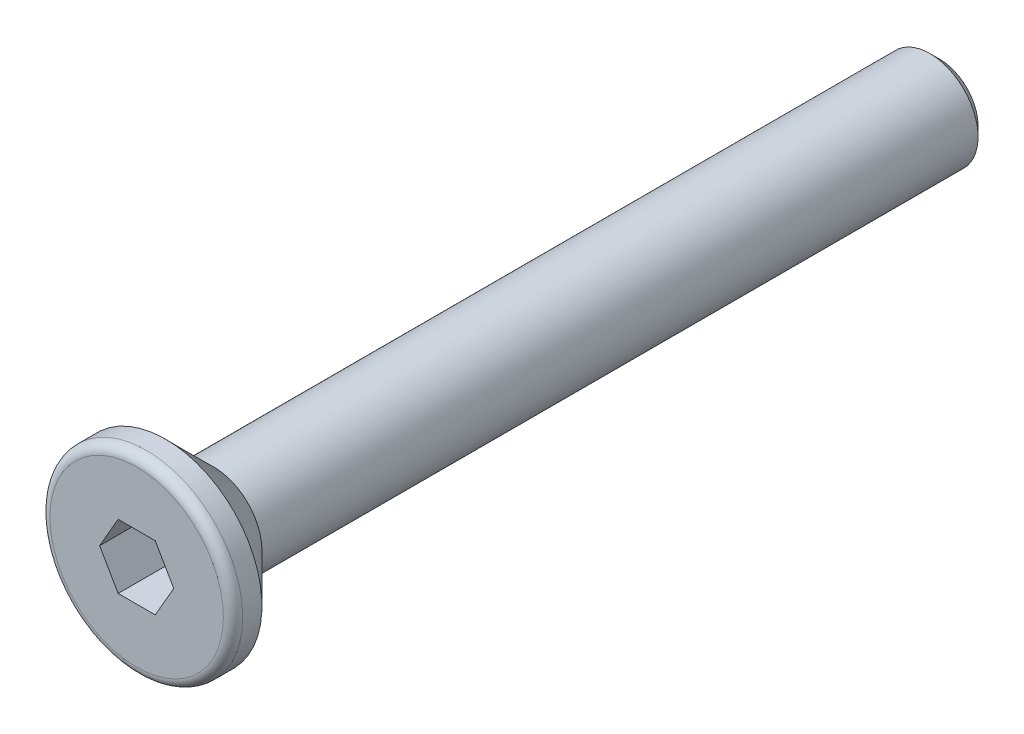
SolidWorks part; units mm, degrees
ref_plane "前视基准面" through (0, 0, 0) normal (0, 0, 1) x (1, 0, 0)
ref_plane "上视基准面" through (0, 0, 0) normal (0, 1, 0) x (1, 0, 0)
ref_plane "右视基准面" through (0, 0, 0) normal (1, 0, 0) x (0, 0, -1)
sketch "草图1" plane through (0, 0, 0) normal (1, 0, 0) x (0, 0, -1)
  line L0 (-12.5, 0) -> (-12.5, 3)
  line L1 (-12.5, 3) -> (-11.6, 3)
  line L2 (-11.6, 3) -> (-10.1, 1.5)
  line L3 (-10.1, 1.5) -> (12.2, 1.5)
  line L4 (12.2, 1.5) -> (12.5, 1.2)
  line L5 (12.5, 1.2) -> (12.5, 0)
  line L6 (12.5, 0) -> (-12.5, 0)
  dimension "D1" = 25
  dimension "D2" = 3
  dimension "D3" = 45
  dimension "D4" = 0.3
  dimension "D5" = 2.4
  dimension "D6" = 1.5
revolve "旋转1" add sketch "草图1" angle 360 about L6
sketch "草图2" plane through (0, 0, 12.5) normal (0, 0, 1) x (1, 0, 0)
  line L1 (1.1547, 0) -> (0.5774, 1)
  line L2 (0.5774, 1) -> (-0.5774, 1)
  line L3 (-0.5774, 1) -> (-1.1547, 0)
  line L4 (-1.1547, 0) -> (-0.5774, -1)
  line L5 (-0.5774, -1) -> (0.5774, -1)
  line L6 (0.5774, -1) -> (1.1547, 0)
  circle A0 centre (0, 0) radius 1 construction
  dimension "D1" = 2
extrude "切除-拉伸1" cut sketch "草图2" against normal blind 1.5
fillet "圆角1" radius 0.3 1 edges at (-3, 0, 12.5)
